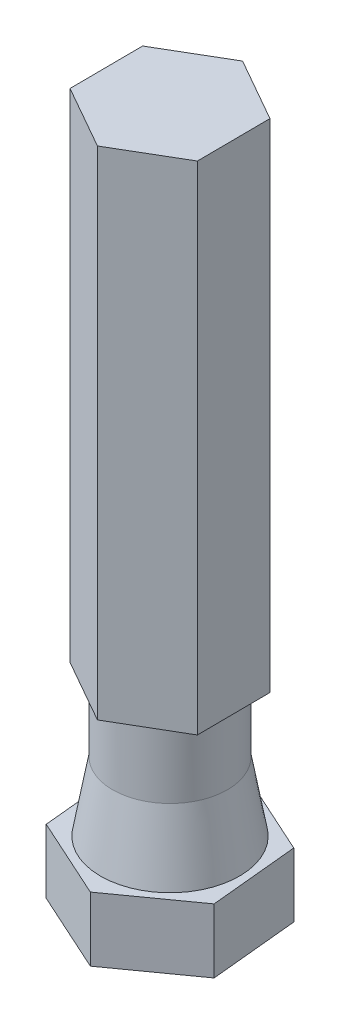
SolidWorks part; units mm, degrees
ref_plane "Front Plane" through (0, 0, 0) normal (0, 0, 1) x (1, 0, 0)
ref_plane "Top Plane" through (0, 0, 0) normal (0, 1, 0) x (1, 0, 0)
ref_plane "Right Plane" through (0, 0, 0) normal (1, 0, 0) x (0, 0, -1)
sketch "Sketch1" plane through (0, 0, 0) normal (0, 1, 0) x (1, 0, 0)
  line L1 (-17.2998, 3.2284) -> (-26.2368, 7.2859)
  line L2 (-26.2368, 7.2859) -> (-34.2192, 1.5749)
  line L3 (-34.2192, 1.5749) -> (-33.2646, -8.1935)
  line L4 (-33.2646, -8.1935) -> (-24.3275, -12.251)
  line L5 (-24.3275, -12.251) -> (-16.3452, -6.54)
  line L6 (-16.3452, -6.54) -> (-17.2998, 3.2284)
  line L7 (-19.6303, -5.0485) -> (-20.2341, 1.1291)
  line L8 (-20.2341, 1.1291) -> (-25.8859, 3.6951)
  line L9 (-25.8859, 3.6951) -> (-30.9341, 0.0834)
  line L10 (-30.9341, 0.0834) -> (-30.3303, -6.0942)
  line L11 (-30.3303, -6.0942) -> (-24.6785, -8.6602)
  line L12 (-24.6785, -8.6602) -> (-19.6303, -5.0485)
  circle A0 centre (-25.2822, -2.4825) radius 8.5 construction
  circle A1 centre (-25.2822, -2.4825) radius 5.3755 construction
  point P1 (-38.0894, -11.6454)
  dimension "D1" = 10.7
extrude "Boss-Extrude1" add sketch "Sketch1" along normal blind 7.1
sketch "Sketch2" plane through (0, 7.1, 0) normal (0, 1, 0) x (1, 0, 0)
  line L0 (-26.2368, 7.2859) -> (-24.3275, -12.251) construction
  line L1 (-24.3275, -12.251) -> (-33.2646, -8.1935) construction
  line L2 (-33.2646, -8.1935) -> (-17.2998, 3.2284) construction
  circle A0 centre (-25.2822, -2.4825) radius 7.6825
  circle A1 centre (-25.2822, -2.4825) radius 1.75
extrude "Boss-Extrude3" add sketch "Sketch2" along normal blind 7.6 draft 10 contours A1 | A0
sketch "Sketch6" plane through (0, 14.7, 0) normal (0, 1, 0) x (1, 0, 0)
  circle A0 centre (-25.2822, -2.4825) radius 6.3424
extrude "Boss-Extrude6" add sketch "Sketch6" along normal blind 7.6
sketch "Sketch7" plane through (0, 22.3, 0) normal (0, 1, 0) x (1, 0, 0)
  line L1 (-18.2552, -6.4773) -> (-18.3091, 1.6056)
  line L2 (-18.3091, 1.6056) -> (-25.3361, 5.6004)
  line L3 (-25.3361, 5.6004) -> (-32.3091, 1.5122)
  line L4 (-32.3091, 1.5122) -> (-32.2552, -6.5707)
  line L5 (-32.2552, -6.5707) -> (-25.2283, -10.5654)
  line L6 (-25.2283, -10.5654) -> (-18.2552, -6.4773)
  circle A0 centre (-25.2822, -2.4825) radius 7.0002 construction
  dimension "D1" = 14
extrude "Boss-Extrude7" add sketch "Sketch7" along normal blind 55
